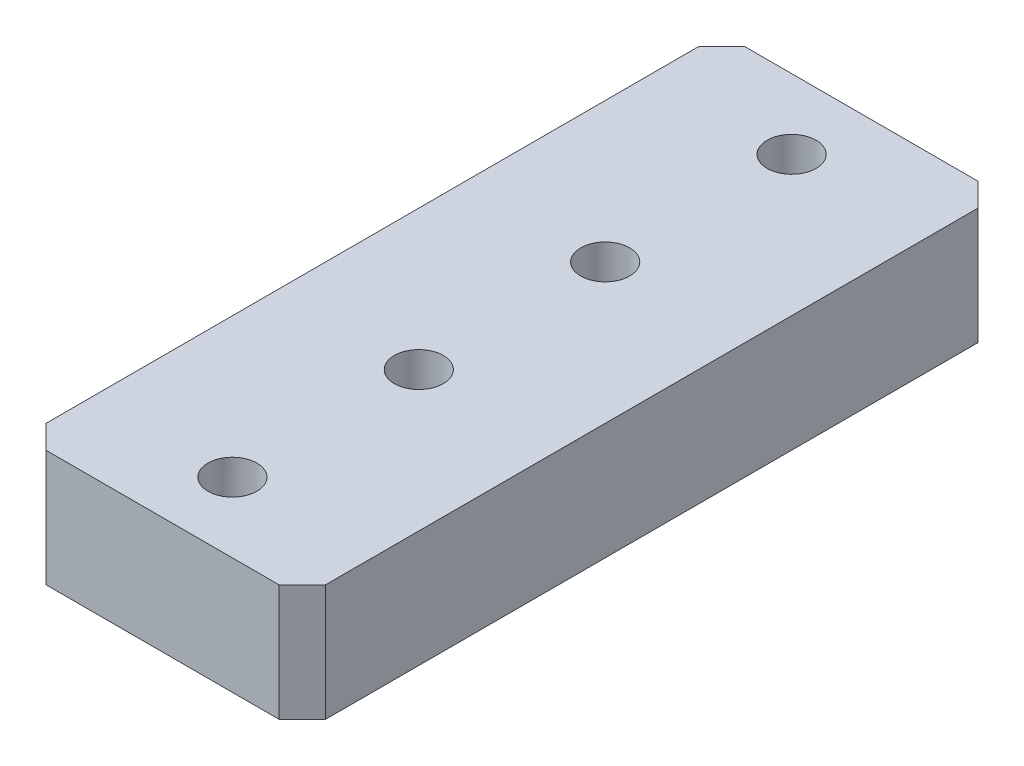
SolidWorks part; units mm, degrees
ref_plane "前视基准面" through (0, 0, 0) normal (0, 0, 1) x (1, 0, 0)
ref_plane "上视基准面" through (0, 0, 0) normal (0, 1, 0) x (1, 0, 0)
ref_plane "右视基准面" through (0, 0, 0) normal (1, 0, 0) x (0, 0, -1)
sketch "草图1" plane through (0, 0, 0) normal (0, 1, 0) x (1, 0, 0)
  line L1 (-12, 30) -> (12, 30)
  line L2 (-12, 30) -> (-12, -30)
  line L3 (-12, -30) -> (12, -30)
  line L4 (12, 30) -> (12, -30)
  line L5 (-12, 30) -> (12, -30) construction
  line L6 (-12, -30) -> (12, 30) construction
  point P0 (0, 0)
extrude "凸台-拉伸1" add sketch "草图1" along normal blind 10
chamfer "倒角1" distance 2 angle 45 4 edges at (-12, 5, -30) (12, 5, -30) (12, 5, 30) (-12, 5, 30)
sketch "草图3" plane through (0, 10, 0) normal (0, 1, 0) x (1, 0, 0)
  circle A0 centre (0, -8) radius 2.1
  circle A1 centre (0, 8) radius 2.1
  circle A2 centre (0, -24) radius 2.1
  circle A3 centre (0, 24) radius 2.1
extrude "切除-拉伸1" cut sketch "草图3" against normal blind 15
sketch "草图4" plane through (0, 0, 0) normal (0, -1, 0) x (1, 0, 0)
  circle A0 centre (0, -24) radius 5
  circle A1 centre (0, -8) radius 5
  circle A2 centre (0, 8) radius 5
  circle A3 centre (0, 24) radius 5
extrude "切除-拉伸2" cut sketch "草图4" against normal blind 6
